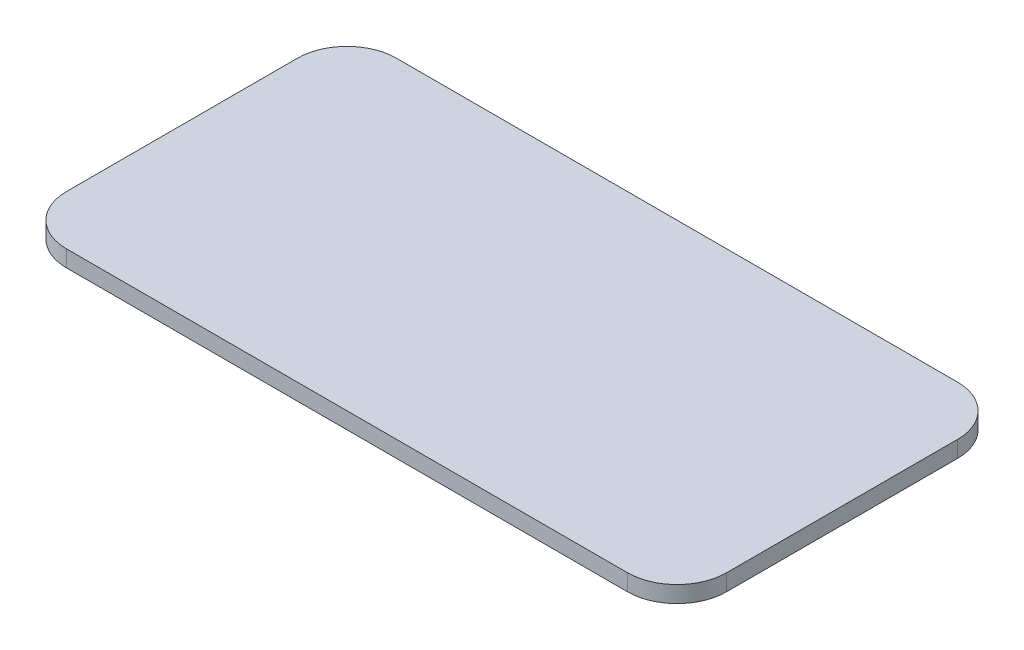
SolidWorks part; units mm, degrees
ref_plane "Front Plane" through (0, 0, 0) normal (0, 0, 1) x (1, 0, 0)
ref_plane "Top Plane" through (0, 0, 0) normal (0, 1, 0) x (1, 0, 0)
ref_plane "Right Plane" through (0, 0, 0) normal (1, 0, 0) x (0, 0, -1)
sketch "Sketch1" plane through (0, 0, 0) normal (0, 1, 0) x (1, 0, 0)
  line L1 (-95.015, 45.015) -> (95.015, 45.015)
  line L2 (-95.015, 45.015) -> (-95.015, -45.015)
  line L3 (-95.015, -45.015) -> (95.015, -45.015)
  line L4 (95.015, 45.015) -> (95.015, -45.015)
  line L5 (-95.015, 45.015) -> (95.015, -45.015) construction
  line L6 (-95.015, -45.015) -> (95.015, 45.015) construction
  line L7 (-92.015, -42.015) -> (92.015, -42.015)
  line L8 (-92.015, -42.015) -> (-92.015, 42.015)
  line L9 (-92.015, 42.015) -> (92.015, 42.015)
  line L10 (92.015, -42.015) -> (92.015, 42.015)
  line L11 (-92.015, -42.015) -> (92.015, 42.015) construction
  line L12 (-92.015, 42.015) -> (92.015, -42.015) construction
  point P0 (0, 0)
  point P5 (0, 0)
  dimension "D1" = 190.03
  dimension "D2" = 90.03
  dimension "D3" = 3
  dimension "D4" = 3
extrude "Boss-Extrude1" add sketch "Sketch1" along normal blind 4
sketch "Sketch2" plane through (0, 4, 0) normal (0, 1, 0) x (1, 0, 0)
  line L1 (-100, 50) -> (100, 50)
  line L2 (-100, 50) -> (-100, -50)
  line L3 (-100, -50) -> (100, -50)
  line L4 (100, 50) -> (100, -50)
  line L5 (-100, 50) -> (100, -50) construction
  line L6 (-100, -50) -> (100, 50) construction
  point P0 (0, 0)
  dimension "D1" = 200
  dimension "D2" = 100
extrude "Boss-Extrude2" add sketch "Sketch2" along normal blind 5
fillet "Fillet1" radius 15 12 edges at (92.015, 2, -42.015) (95.015, 2, -45.015) (-92.015, 2, -42.015) (-95.015, 2, -45.015) (-92.015, 2, 42.015) (-95.015, 2, 45.015) (95.015, 2, 45.015) (92.015, 2, 42.015) (100, 6.5, -50) (100, 6.5, 50) (-100, 6.5, -50) (-100, 6.5, 50)
